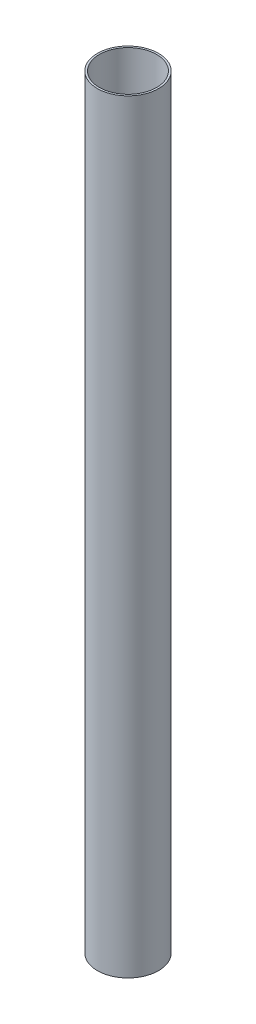
SolidWorks part; units mm, degrees
ref_plane "前视基准面" through (0, 0, 0) normal (0, 0, 1) x (1, 0, 0)
ref_plane "上视基准面" through (0, 0, 0) normal (0, 1, 0) x (1, 0, 0)
ref_plane "右视基准面" through (0, 0, 0) normal (1, 0, 0) x (0, 0, -1)
other "Configuration Table"
sketch "草图1" plane through (0, 0, 0) normal (0, 1, 0) x (1, 0, 0)
  circle A0 centre (0, 0) radius 7.5
  circle A1 centre (0, 0) radius 8
  dimension "D1" = 16
  dimension "D2" = 15
extrude "凸台-拉伸1" add sketch "草图1" along normal blind 200
